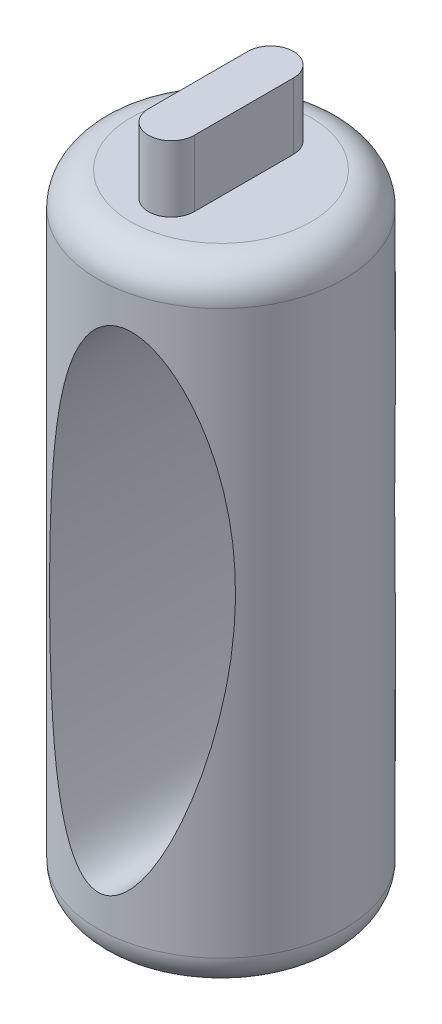
SolidWorks part; units mm, degrees
ref_plane "Спереди" through (0, 0, 0) normal (0, 0, 1) x (1, 0, 0)
ref_plane "Сверху" through (0, 0, 0) normal (0, 1, 0) x (1, 0, 0)
ref_plane "Справа" through (0, 0, 0) normal (1, 0, 0) x (0, 0, -1)
sketch "Эскиз1" plane through (0, 0, 0) normal (0, 1, 0) x (1, 0, 0)
  circle A0 centre (0, 0) radius 7.45
extrude "Бобышка-Вытянуть1" add sketch "Эскиз1" along normal blind 38
fillet "Скругление1" radius 2 2 edges at (0, 38, 7.45) (0, 0, 7.45)
sketch "Эскиз2" plane through (0, 0, 0) normal (0, 0, 1) x (1, 0, 0)
  line L0 (-7.45, 36) -> (8.9249, 2) construction
  line L1 (7.45, 2) -> (-7.45, 2) construction
  ellipse E0 centre (0.7374, 19) end of major axis (-0.0376, 3.9269) minor radius 4.8967
extrude "Вырез-Вытянуть1" cut sketch "Эскиз2" against normal through all both and the other way through all
sketch "Эскиз3" plane through (0, 38, 0) normal (0, 1, 0) x (1, 0, 0)
  line L0 (0, 3) -> (0, -3) construction
  line L1 (1.3857, 3) -> (1.3857, -3)
  line L2 (-1.3857, 3) -> (-1.3857, -3)
  arc A0 (1.3857, 3) -> (-1.3857, 3) centre (0, 3) ccw
  arc A1 (-1.3857, -3) -> (1.3857, -3) centre (0, -3) ccw
  point P2 (0, 0)
extrude "凸台-拉伸1" add sketch "Эскиз3" along normal blind 4 separate body
